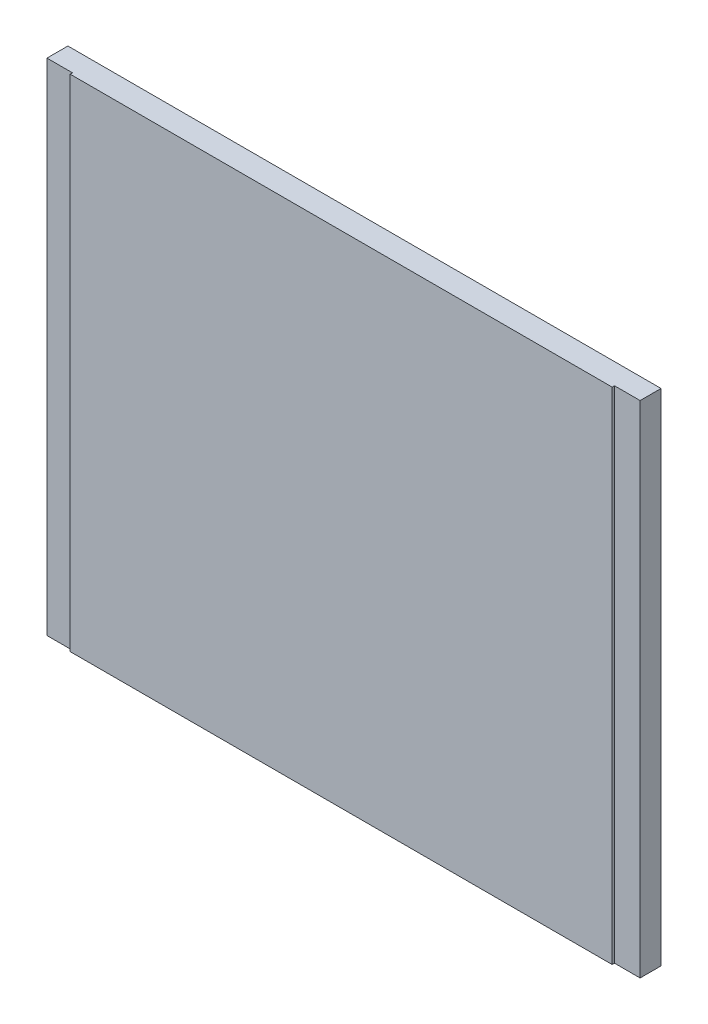
SolidWorks part; units mm, degrees
ref_plane "Plan de face" through (0, 0, 0) normal (0, 0, 1) x (1, 0, 0)
ref_plane "Plan de dessus" through (0, 0, 0) normal (0, 1, 0) x (1, 0, 0)
ref_plane "Plan de droite" through (0, 0, 0) normal (1, 0, 0) x (0, 0, -1)
sketch "Esquisse1" plane through (0, 0, 0) normal (0, 0, 1) x (1, 0, 0)
  line L1 (-127.5, 107.5) -> (127.5, 107.5)
  line L2 (-127.5, 107.5) -> (-127.5, -107.5)
  line L3 (-127.5, -107.5) -> (127.5, -107.5)
  line L4 (127.5, 107.5) -> (127.5, -107.5)
  line L5 (-127.5, 107.5) -> (127.5, -107.5) construction
  line L6 (-127.5, -107.5) -> (127.5, 107.5) construction
  point P0 (0, 0)
  dimension "D1" = 255
  dimension "D2" = 215
extrude "Boss.-Extru.1" add sketch "Esquisse1" along normal blind 10
sketch "Esquisse2" plane through (0, 0, 10) normal (0, 0, 1) x (1, 0, 0)
  line L1 (-127.5, 107.5) -> (127.5, 107.5)
  line L2 (-127.5, 107.5) -> (-127.5, -107.5)
  line L3 (-127.5, -107.5) -> (127.5, -107.5)
  line L4 (127.5, 107.5) -> (127.5, -107.5)
  line L5 (-127.5, 107.5) -> (127.5, -107.5) construction
  line L6 (-127.5, -107.5) -> (127.5, 107.5) construction
  line L7 (-116.5, 107.5) -> (116.5, 107.5)
  line L8 (-116.5, 107.5) -> (-116.5, -107.5)
  line L9 (-116.5, -107.5) -> (116.5, -107.5)
  line L10 (116.5, 107.5) -> (116.5, -107.5)
  line L11 (-116.5, 107.5) -> (116.5, -107.5) construction
  line L12 (-116.5, -107.5) -> (116.5, 107.5) construction
  point P0 (0, 0)
  point P7 (0, 0)
  line M9 (127.5, -107.5) -> (127.5, 107.5)
  line M10 (127.5, 107.5) -> (-127.5, 107.5)
  line M11 (-127.5, 107.5) -> (-127.5, -107.5)
  line M12 (-127.5, -107.5) -> (127.5, -107.5)
  dimension "D1" = 11
  dimension "D2" = 0
extrude "Enlèv. mat.-Extru.1" cut sketch "Esquisse2" against normal blind 1 contours L8 M10 M11 M12 | L10 M10 M12 M9
